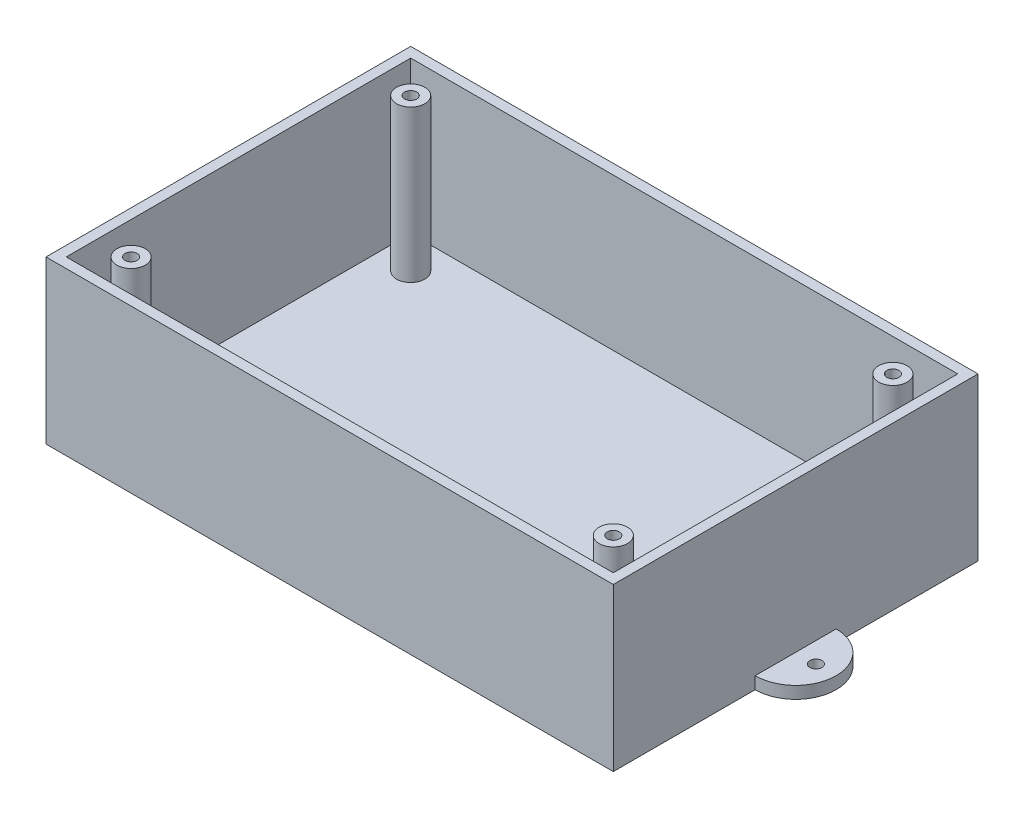
SolidWorks part; units mm, degrees
ref_plane "Front Plane" through (0, 0, 0) normal (0, 0, 1) x (1, 0, 0)
ref_plane "Top Plane" through (0, 0, 0) normal (0, 1, 0) x (1, 0, 0)
ref_plane "Right Plane" through (0, 0, 0) normal (1, 0, 0) x (0, 0, -1)
sketch "Sketch1" plane through (0, 0, 0) normal (0, 1, 0) x (1, 0, 0)
  line L1 (0, 0) -> (140, 0)
  line L2 (0, 0) -> (0, 90)
  line L3 (0, 90) -> (140, 90)
  line L4 (140, 0) -> (140, 90)
  dimension "D1" = 140
  dimension "D2" = 90
extrude "Boss-Extrude1" add sketch "Sketch1" along normal blind 40
sketch "Sketch2" plane through (0, 40, 0) normal (0, 1, 0) x (1, 0, 0)
  line L0 (0, 0) -> (140, 90) construction
  line L1 (0, 90) -> (140, 0) construction
  line L2 (140, 90) -> (0, 90) construction
  line L3 (2.5, 87.5) -> (137.5, 87.5)
  line L4 (2.5, 87.5) -> (2.5, 2.5)
  line L5 (2.5, 2.5) -> (137.5, 2.5)
  line L6 (137.5, 87.5) -> (137.5, 2.5)
  line L7 (2.5, 87.5) -> (137.5, 2.5) construction
  line L8 (2.5, 2.5) -> (137.5, 87.5) construction
  line L9 (0, 90) -> (0, 0) construction
  point P8 (70, 45)
  dimension "D1" = 2.5
  dimension "D2" = 2.5
extrude "Cut-Extrude1" cut sketch "Sketch2" against normal blind 37.5
sketch "Sketch3" plane through (0, 2.5, 0) normal (0, 1, 0) x (1, 0, 0)
  line L0 (137.5, 2.5) -> (137.5, 87.5) construction
  line L1 (2.5, 2.5) -> (137.5, 2.5) construction
  line L2 (137.5, 87.5) -> (2.5, 87.5) construction
  line L3 (2.5, 87.5) -> (2.5, 2.5) construction
  circle A0 centre (10.5, 79.5) radius 3.5
  circle A1 centre (10.5, 10.5) radius 3.5
  circle A2 centre (129.5, 10.5) radius 3.5
  circle A3 centre (129.5, 79.5) radius 3.5
  dimension "D5" = 7
  dimension "D6" = 7
  dimension "D7" = 7
  dimension "D8" = 7
  dimension "D1" = 8
  dimension "D2" = 8
  dimension "D3" = 8
  dimension "D4" = 8
extrude "Boss-Extrude2" add sketch "Sketch3" along normal blind 37.5
sketch "Sketch4" plane through (0, 40, 0) normal (0, 1, 0) x (1, 0, 0)
  line L0 (10.5, 79.5) -> (129.5, 79.5) construction
  line L1 (10.5, 10.5) -> (129.5, 10.5) construction
  circle A0 centre (10.5, 79.5) radius 1.5
  circle A1 centre (129.5, 79.5) radius 1.5
  circle A2 centre (10.5, 10.5) radius 1.5
  circle A3 centre (129.5, 10.5) radius 1.5
  dimension "D1" = 3
  dimension "D2" = 3
  dimension "D3" = 3
  dimension "D4" = 3
extrude "Cut-Extrude2" cut sketch "Sketch4" against normal blind 37.5
sketch "Sketch5" plane through (0, 0, 0) normal (0, -1, 0) x (1, 0, 0)
  line L0 (-38.6002, -45) -> (170.0883, -45)
  line L1 (0, -90) -> (0, 0) construction
  line L2 (140, 0) -> (140, -90) construction
  line L3 (0, -35) -> (0, -55)
  line L4 (140, -35) -> (140, -55)
  arc A0 (0, -55) -> (0, -35) centre (0, -45) cw
  arc A1 (140, -55) -> (140, -35) centre (140, -45) ccw
  line M1 (0, 0) -> (0, -90)
  line M3 (140, -90) -> (140, 0)
  dimension "D1" = 10
  dimension "D2" = 10
extrude "Boss-Extrude3" add sketch "Sketch5" against normal blind 3 contours A0 L0 M1 | A0 L0 M1 | L0 A1 M3 | A1 L0 M3
sketch "Sketch7" plane through (0, 0, 0) normal (0, -1, 0) x (1, 0, 0)
  circle A0 centre (-5, -45) radius 1.5
  circle A1 centre (145, -45) radius 1.5
  arc A2 (0, -35) -> (0, -55) centre (0, -45) ccw construction
  arc A3 (140, -55) -> (140, -35) centre (140, -45) ccw construction
  point P8 (-10, -45)
  point P13 (150, -45)
  dimension "D1" = 3
  dimension "D2" = 3
  dimension "D3" = 5
  dimension "D4" = 5
extrude "Cut-Extrude3" cut sketch "Sketch7" against normal through all
